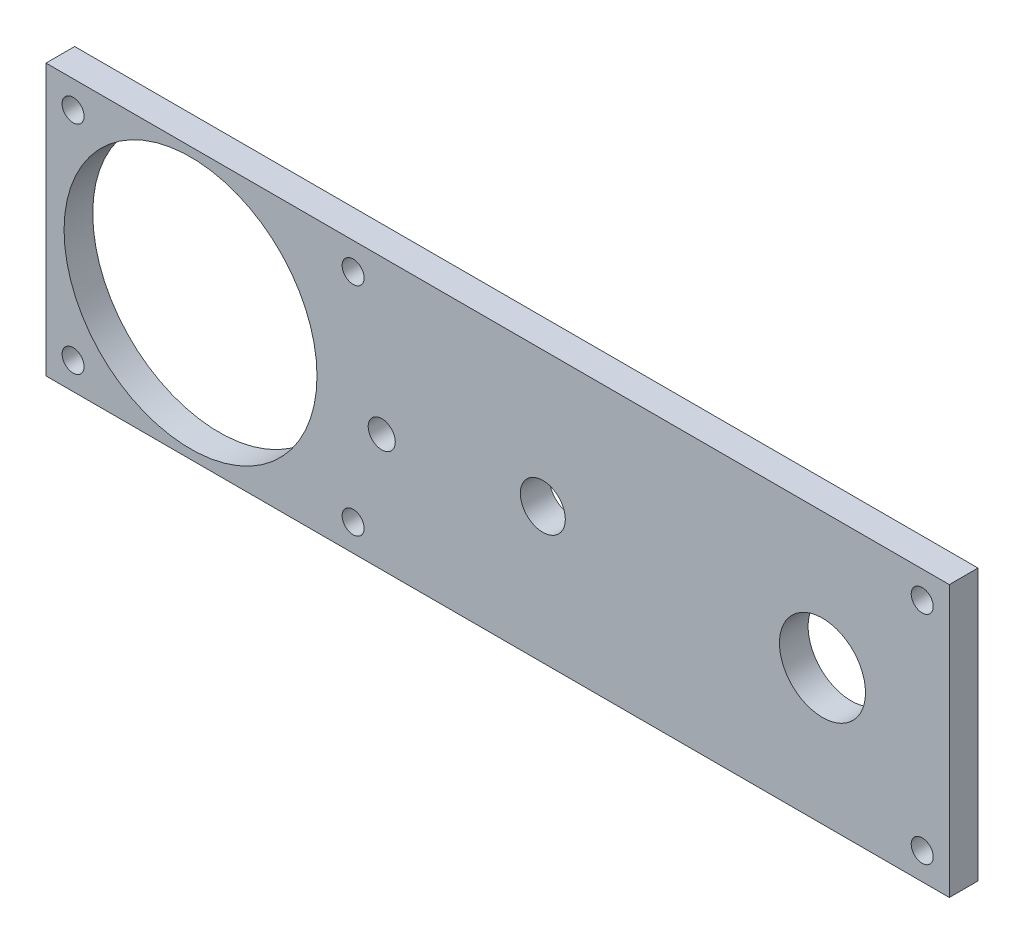
SolidWorks part; units mm, degrees
ref_plane "Front Plane" through (0, 0, 0) normal (0, 0, 1) x (1, 0, 0)
ref_plane "Top Plane" through (0, 0, 0) normal (0, 1, 0) x (1, 0, 0)
ref_plane "Right Plane" through (0, 0, 0) normal (1, 0, 0) x (0, 0, -1)
sketch "Sketch1" plane through (0, 0, 0) normal (0, 0, 1) x (1, 0, 0)
  line L0 (100, 15) -> (0, 15) construction
  line L1 (0, 0) -> (100, 0)
  line L2 (0, 0) -> (0, 30)
  line L3 (0, 30) -> (100, 30)
  line L4 (100, 0) -> (100, 30)
  circle A0 centre (55, 15) radius 2.4892
  circle A1 centre (37.1667, 13) radius 1.4986
  circle A2 centre (25.1698, 20.9334) radius 0.9906 construction
  circle A3 centre (37.1667, 13) radius 11.4777 construction
  circle A4 centre (25.1698, 20.9334) radius 7.1501 construction
  circle A5 centre (55, 15) radius 12.827 construction
  circle A6 centre (16, 15) radius 14
  circle A7 centre (37.1667, 13) radius 5.1181 construction
  point P7 (55, 15)
  point P8 (37.1667, 13)
  point P9 (25.1698, 20.9334)
  point P19 (16, 15)
  dimension "D6" = 4.9784
  dimension "D7" = 2.9972
  dimension "D8" = 1.9812
  dimension "D9" = 25.654
  dimension "D10" = 22.9553
  dimension "D11" = 14.3002
  dimension "D13" = 28
  dimension "D14" = 10.2362
  dimension "D1" = 17.9451
  dimension "D2" = 14.3828
  dimension "D3" = 30
  dimension "D4" = 100
  dimension "D5" = 55
  dimension "D12" = 10.922
  dimension "D15" = 16
  dimension "D16" = 13
extrude "Boss-Extrude2" add sketch "Sketch1" along normal blind 3.175
hole_wizard "#2 Clearance Hole1" positions "Sketch4" profile "Sketch3" hole size "#2" standard "ANSI Inch" end condition through all
sketch "Sketch4" plane through (0, 0, 3.175) normal (0, 0, 1) x (1, 0, 0)
  line L0 (97, 0) -> (97, 30) construction
  line L1 (0, 0) -> (100, 0) construction
  line L2 (100, 30) -> (0, 30) construction
  line L4 (100, 0) -> (100, 30) construction
  line L5 (3, 30) -> (3, 0) construction
  line L7 (0, 30) -> (0, 0) construction
  line L8 (34, 30) -> (34, 0) construction
  point P8 (97, 3)
  point P10 (97, 27)
  point P27 (3, 27)
  point P29 (3, 3)
  point P34 (34, 27)
  point P36 (34, 3)
  dimension "D1" = 3
  dimension "D2" = 3
  dimension "D3" = 3
  dimension "D4" = 3
  dimension "D5" = 3
  dimension "D6" = 3
  dimension "D7" = 34
  dimension "D8" = 3
  dimension "D9" = 3
sketch "Sketch3" plane through (97, 3, 3.175) normal (1, 0, 0) x (0, -1, 0)
  line L0 (0, 0) -> (0, 3.175)
  line L1 (0, 3.175) -> (1.2192, 3.175)
  line L2 (1.2192, 3.175) -> (1.2192, 0)
  line L5 (1.2192, 0) -> (0, 0)
  line L11 (0, -6.35) -> (0, 107.95) construction
  dimension "Thru Hole Dia." = 2.4384
  dimension "Thru Hole Depth" = 3.175
sketch "Sketch5" plane through (0, 0, 3.175) normal (0, 0, 1) x (1, 0, 0)
  line L0 (0, 15) -> (100, 15) construction
  line L1 (0, 30) -> (0, 0) construction
  line L2 (100, 0) -> (100, 30) construction
  circle A0 centre (85.9562, 15) radius 4.7625
  circle A1 centre (55, 15) radius 2.4892 construction
  dimension "D1" = 30.9562
  dimension "D2" = 9.525
extrude "Cut-Extrude1" cut sketch "Sketch5" against normal through all
